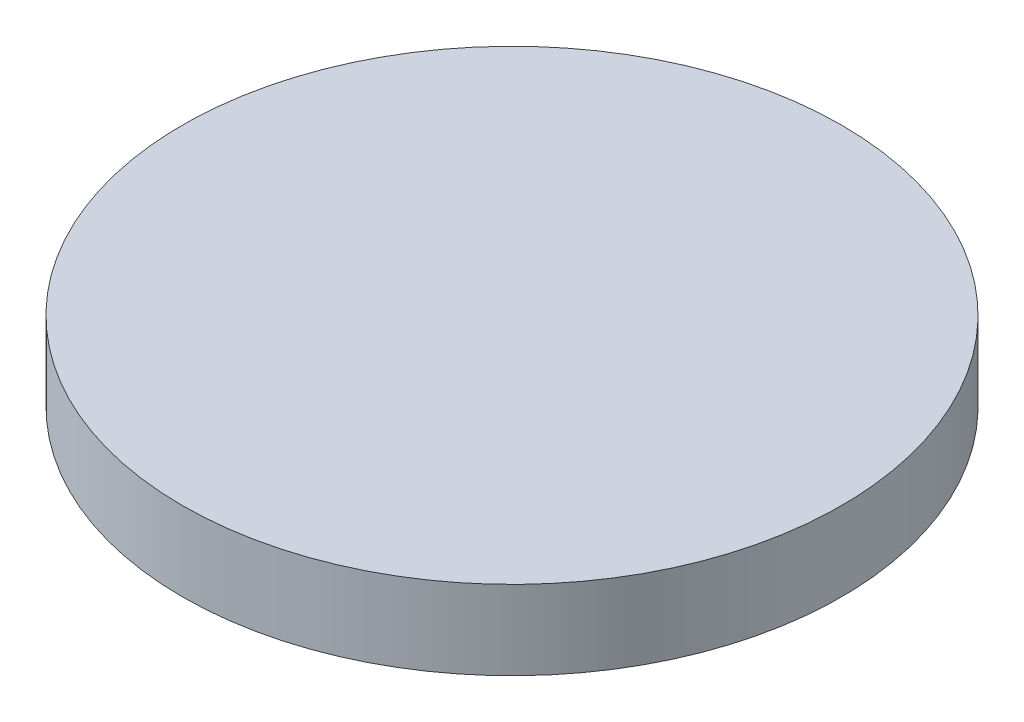
SolidWorks part; units mm, degrees
ref_plane "Plan de face" through (0, 0, 0) normal (0, 0, 1) x (1, 0, 0)
ref_plane "Plan de dessus" through (0, 0, 0) normal (0, 1, 0) x (1, 0, 0)
ref_plane "Plan de droite" through (0, 0, 0) normal (1, 0, 0) x (0, 0, -1)
sketch "Esquisse1" plane through (0, 0, 0) normal (0, 1, 0) x (1, 0, 0)
  circle A0 centre (31.4761, 27.7416) radius 150
  dimension "D1" = 300
extrude "Boss.-Extru.1" add sketch "Esquisse1" along normal blind 36
sketch "Esquisse2" plane through (0, 36, 0) normal (0, 1, 0) x (1, 0, 0)
  circle A0 centre (31.4761, 27.7416) radius 150 construction
  point P0 (31.4761, 177.7416)
  point P1 (31.4761, 27.7416)
